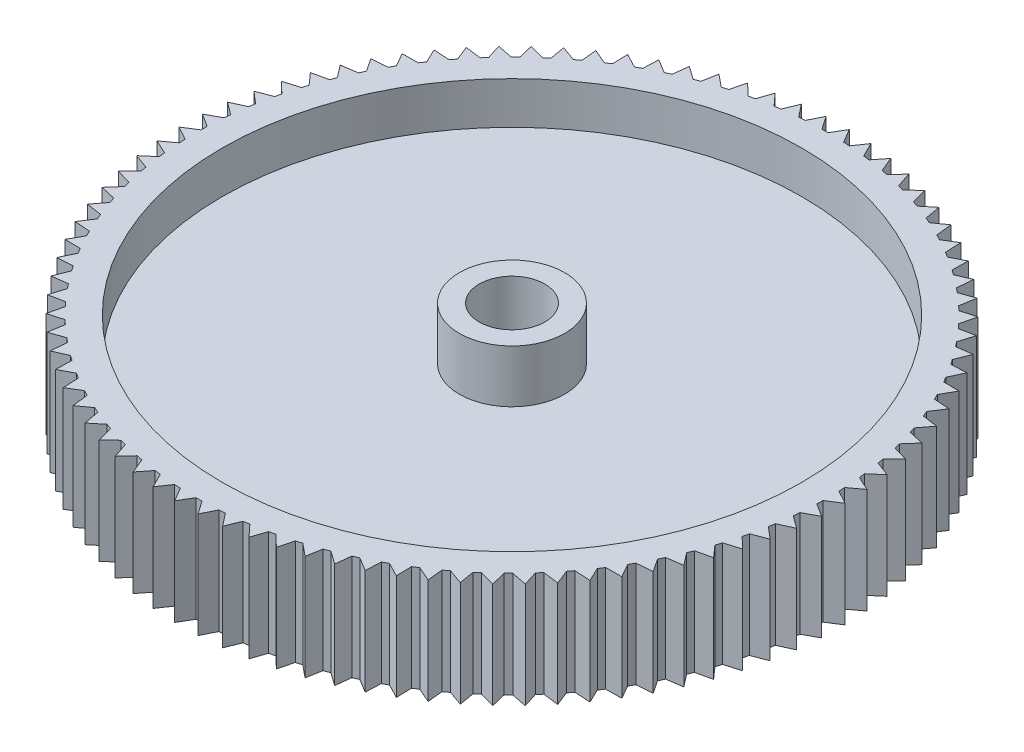
SolidWorks part; units mm, degrees
ref_plane "Front Plane" through (0, 0, 0) normal (0, 0, 1) x (1, 0, 0)
ref_plane "Top Plane" through (0, 0, 0) normal (0, 1, 0) x (1, 0, 0)
ref_plane "Right Plane" through (0, 0, 0) normal (1, 0, 0) x (0, 0, -1)
sketch "Sketch1" plane through (0, 0, 0) normal (0, 1, 0) x (1, 0, 0)
  circle A0 centre (0, 0) radius 12.0584
extrude "Boss-Extrude1" add sketch "Sketch1" along normal blind 10
ref_plane "Plane1" through (0, 5, 0) normal (0, 1, 0) x (1, 0, 0)
sketch "Sketch2" plane through (0, 5, 0) normal (0, 1, 0) x (1, 0, 0)
  circle A0 centre (0, 0) radius 30
  dimension "D1" = 60
extrude "Boss-Extrude3" add sketch "Sketch2" along normal mid plane 10 contours A0
sketch "Sketch3" plane through (0, 10, 0) normal (0, 1, 0) x (1, 0, 0)
  circle A0 centre (0, 0) radius 27.5
  dimension "D1" = 55
extrude "Cut-Extrude1" cut sketch "Sketch3" against normal blind 4
sketch "Sketch4" plane through (0, 0, 0) normal (0, -1, 0) x (1, 0, 0)
  circle A0 centre (0, 0) radius 27.5
  dimension "D1" = 55
extrude "Cut-Extrude2" cut sketch "Sketch4" against normal blind 4
sketch "Sketch5" plane through (0, 6, 0) normal (0, 1, 0) x (1, 0, 0)
  circle A0 centre (0, 0) radius 5
  circle A1 centre (0, 0) radius 3
  dimension "D1" = 10
  dimension "D2" = 6
extrude "Boss-Extrude4" add sketch "Sketch5" along normal mid plane 10 contours A0
sketch "Sketch6" plane through (0, 1, 0) normal (0, -1, 0) x (1, 0, 0)
  circle A0 centre (0, 0) radius 3.1205
extrude "Cut-Extrude3" cut sketch "Sketch6" against normal blind 10
sketch "Sketch8" plane through (0, 10, 0) normal (0, 1, 0) x (1, 0, 0)
  line L0 (0, 30) -> (0.7466, 31.2704)
  line L1 (0.7466, 31.2704) -> (1.5196, 29.9615)
  line L2 (0, 30) -> (1.5196, 29.9615)
  line L3 (2.9261, 31.1421) -> (3.6059, 29.7825)
  line L4 (2.0927, 29.9269) -> (2.9261, 31.1421)
  line L5 (2.0927, 29.9269) -> (3.6059, 29.7825)
  line L6 (5.0913, 30.8621) -> (5.6747, 29.4584)
  line L7 (4.1752, 29.708) -> (5.0913, 30.8621)
  line L8 (4.1752, 29.708) -> (5.6747, 29.4584)
  line L9 (7.2318, 30.4318) -> (7.7157, 28.9908)
  line L10 (6.2374, 29.3444) -> (7.2318, 30.4318)
  line L11 (6.2374, 29.3444) -> (7.7157, 28.9908)
  line L12 (9.337, 29.8532) -> (9.7192, 28.382)
  line L13 (8.2691, 28.8379) -> (9.337, 29.8532)
  line L14 (8.2691, 28.8379) -> (9.7192, 28.382)
  line L15 (11.3967, 29.1292) -> (11.6754, 27.6349)
  line L16 (10.2606, 28.1908) -> (11.3967, 29.1292)
  line L17 (10.2606, 28.1908) -> (11.6754, 27.6349)
  line L18 (13.4009, 28.2632) -> (13.5747, 26.7531)
  line L19 (12.2021, 27.4064) -> (13.4009, 28.2632)
  line L20 (12.2021, 27.4064) -> (13.5747, 26.7531)
  line L21 (15.3398, 27.2596) -> (15.4078, 25.741)
  line L22 (14.0841, 26.4884) -> (15.3398, 27.2596)
  line L23 (14.0841, 26.4884) -> (15.4078, 25.741)
  line L24 (17.2039, 26.1231) -> (17.1659, 24.6035)
  line L25 (15.8976, 25.4414) -> (17.2039, 26.1231)
  line L26 (15.8976, 25.4414) -> (17.1659, 24.6035)
  line L27 (18.9843, 24.8594) -> (18.8403, 23.3461)
  line L28 (17.6336, 24.2705) -> (18.9843, 24.8594)
  line L29 (17.6336, 24.2705) -> (18.8403, 23.3461)
  line L30 (20.6721, 23.4746) -> (20.423, 21.975)
  line L31 (19.2836, 22.9813) -> (20.6721, 23.4746)
  line L32 (19.2836, 22.9813) -> (20.423, 21.975)
  line L33 (22.2593, 21.9754) -> (21.9061, 20.4969)
  line L34 (20.8398, 21.5802) -> (22.2593, 21.9754)
  line L35 (20.8398, 21.5802) -> (21.9061, 20.4969)
  line L36 (23.738, 20.3691) -> (23.2825, 18.9189)
  line L37 (22.2943, 20.0739) -> (23.738, 20.3691)
  line L38 (22.2943, 20.0739) -> (23.2825, 18.9189)
  line L39 (25.101, 18.6636) -> (24.5455, 17.2487)
  line L40 (23.6403, 18.4698) -> (25.101, 18.6636)
  line L41 (23.6403, 18.4698) -> (24.5455, 17.2487)
  line L42 (26.3418, 16.8672) -> (25.689, 15.4944)
  line L43 (24.8711, 16.7758) -> (26.3418, 16.8672)
  line L44 (24.8711, 16.7758) -> (25.689, 15.4944)
  line L45 (27.4542, 14.9886) -> (26.7072, 13.6647)
  line L46 (25.9808, 15) -> (27.4542, 14.9886)
  line L47 (25.9808, 15) -> (26.7072, 13.6647)
  line L48 (28.4329, 13.037) -> (27.5954, 11.7684)
  line L49 (26.9638, 13.1511) -> (28.4329, 13.037)
  line L50 (26.9638, 13.1511) -> (27.5954, 11.7684)
  line L51 (29.2731, 11.0219) -> (28.3491, 9.8148)
  line L52 (27.8155, 11.2382) -> (29.2731, 11.0219)
  line L53 (27.8155, 11.2382) -> (28.3491, 9.8148)
  line L54 (29.9706, 8.953) -> (28.9647, 7.8134)
  line L55 (28.5317, 9.2705) -> (29.9706, 8.953)
  line L56 (28.5317, 9.2705) -> (28.9647, 7.8134)
  line L57 (30.5221, 6.8406) -> (29.4391, 5.7739)
  line L58 (29.1089, 7.2577) -> (30.5221, 6.8406)
  line L59 (29.1089, 7.2577) -> (29.4391, 5.7739)
  line L60 (30.9249, 4.6948) -> (29.7702, 3.7062)
  line L61 (29.5442, 5.2094) -> (30.9249, 4.6948)
  line L62 (29.5442, 5.2094) -> (29.7702, 3.7062)
  line L63 (31.1771, 2.5261) -> (29.9562, 1.6205)
  line L64 (29.8357, 3.1359) -> (31.1771, 2.5261)
  line L65 (29.8357, 3.1359) -> (29.9562, 1.6205)
  line L66 (31.2774, 0.3452) -> (29.9963, -0.473)
  line L67 (29.9817, 1.047) -> (31.2774, 0.3452)
  line L68 (29.9817, 1.047) -> (29.9963, -0.473)
  line L69 (31.2253, -1.8375) -> (29.8902, -2.5643)
  line L70 (29.9817, -1.047) -> (31.2253, -1.8375)
  line L71 (29.9817, -1.047) -> (29.8902, -2.5643)
  line L72 (31.021, -4.0111) -> (29.6385, -4.6431)
  line L73 (29.8357, -3.1359) -> (31.021, -4.0111)
  line L74 (29.8357, -3.1359) -> (29.6385, -4.6431)
  line L75 (30.6656, -6.1653) -> (29.2424, -6.6993)
  line L76 (29.5442, -5.2094) -> (30.6656, -6.1653)
  line L77 (29.5442, -5.2094) -> (29.2424, -6.6993)
  line L78 (30.1609, -8.2894) -> (28.7039, -8.7228)
  line L79 (29.1089, -7.2577) -> (30.1609, -8.2894)
  line L80 (29.1089, -7.2577) -> (28.7039, -8.7228)
  line L81 (29.5092, -10.3731) -> (28.0255, -10.7038)
  line L82 (28.5317, -9.2705) -> (29.5092, -10.3731)
  line L83 (28.5317, -9.2705) -> (28.0255, -10.7038)
  line L84 (28.7137, -12.4063) -> (27.2106, -12.6327)
  line L85 (27.8155, -11.2382) -> (28.7137, -12.4063)
  line L86 (27.8155, -11.2382) -> (27.2106, -12.6327)
  line L87 (27.7783, -14.3791) -> (26.2631, -14.5001)
  line L88 (26.9638, -13.1511) -> (27.7783, -14.3791)
  line L89 (26.9638, -13.1511) -> (26.2631, -14.5001)
  line L90 (26.7076, -16.2818) -> (25.1876, -16.2968)
  line L91 (25.9808, -15) -> (26.7076, -16.2818)
  line L92 (25.9808, -15) -> (25.1876, -16.2968)
  line L93 (25.5068, -18.1051) -> (23.9894, -18.0141)
  line L94 (24.8711, -16.7758) -> (25.5068, -18.1051)
  line L95 (24.8711, -16.7758) -> (23.9894, -18.0141)
  line L96 (24.1817, -19.8403) -> (22.6744, -19.6436)
  line L97 (23.6403, -18.4698) -> (24.1817, -19.8403)
  line L98 (23.6403, -18.4698) -> (22.6744, -19.6436)
  line L99 (22.7388, -21.4788) -> (21.2489, -21.1774)
  line L100 (22.2943, -20.0739) -> (22.7388, -21.4788)
  line L101 (22.2943, -20.0739) -> (21.2489, -21.1774)
  line L102 (21.1852, -23.0126) -> (19.7199, -22.6081)
  line L103 (20.8398, -21.5802) -> (21.1852, -23.0126)
  line L104 (20.8398, -21.5802) -> (19.7199, -22.6081)
  line L105 (19.5283, -24.4344) -> (18.0948, -23.9286)
  line L106 (19.2836, -22.9813) -> (19.5283, -24.4344)
  line L107 (19.2836, -22.9813) -> (18.0948, -23.9286)
  line L108 (17.7762, -25.7371) -> (16.3815, -25.1326)
  line L109 (17.6336, -24.2705) -> (17.7762, -25.7371)
  line L110 (17.6336, -24.2705) -> (16.3815, -25.1326)
  line L111 (15.9376, -26.9144) -> (14.5885, -26.2141)
  line L112 (15.8976, -25.4414) -> (15.9376, -26.9144)
  line L113 (15.8976, -25.4414) -> (14.5885, -26.2141)
  line L114 (14.0213, -27.9606) -> (12.7243, -27.1678)
  line L115 (14.0841, -26.4884) -> (14.0213, -27.9606)
  line L116 (14.0841, -26.4884) -> (12.7243, -27.1678)
  line L117 (12.0368, -28.8706) -> (10.7982, -27.9893)
  line L118 (12.2021, -27.4064) -> (12.0368, -28.8706)
  line L119 (12.2021, -27.4064) -> (10.7982, -27.9893)
  line L120 (9.9935, -29.6399) -> (8.8195, -28.6743)
  line L121 (10.2606, -28.1908) -> (9.9935, -29.6399)
  line L122 (10.2606, -28.1908) -> (8.8195, -28.6743)
  line L123 (7.9016, -30.2648) -> (6.7978, -29.2197)
  line L124 (8.2691, -28.8379) -> (7.9016, -30.2648)
  line L125 (8.2691, -28.8379) -> (6.7978, -29.2197)
  line L126 (5.7712, -30.7423) -> (4.7429, -29.6227)
  line L127 (6.2374, -29.3444) -> (5.7712, -30.7423)
  line L128 (6.2374, -29.3444) -> (4.7429, -29.6227)
  line L129 (3.6127, -31.0699) -> (2.665, -29.8814)
  line L130 (4.1752, -29.708) -> (3.6127, -31.0699)
  line L131 (4.1752, -29.708) -> (2.665, -29.8814)
  line L132 (1.4365, -31.2463) -> (0.5741, -29.9945)
  line L133 (2.0927, -29.9269) -> (1.4365, -31.2463)
  line L134 (2.0927, -29.9269) -> (0.5741, -29.9945)
  line L135 (-0.7466, -31.2704) -> (-1.5196, -29.9615)
  line L136 (0, -30) -> (-0.7466, -31.2704)
  line L137 (0, -30) -> (-1.5196, -29.9615)
  line L138 (-2.9261, -31.1421) -> (-3.6059, -29.7825)
  line L139 (-2.0927, -29.9269) -> (-2.9261, -31.1421)
  line L140 (-2.0927, -29.9269) -> (-3.6059, -29.7825)
  line L141 (-5.0913, -30.8621) -> (-5.6747, -29.4584)
  line L142 (-4.1752, -29.708) -> (-5.0913, -30.8621)
  line L143 (-4.1752, -29.708) -> (-5.6747, -29.4584)
  line L144 (-7.2318, -30.4318) -> (-7.7157, -28.9908)
  line L145 (-6.2374, -29.3444) -> (-7.2318, -30.4318)
  line L146 (-6.2374, -29.3444) -> (-7.7157, -28.9908)
  line L147 (-9.337, -29.8532) -> (-9.7192, -28.382)
  line L148 (-8.2691, -28.8379) -> (-9.337, -29.8532)
  line L149 (-8.2691, -28.8379) -> (-9.7192, -28.382)
  line L150 (-11.3967, -29.1292) -> (-11.6754, -27.6349)
  line L151 (-10.2606, -28.1908) -> (-11.3967, -29.1292)
  line L152 (-10.2606, -28.1908) -> (-11.6754, -27.6349)
  line L153 (-13.4009, -28.2632) -> (-13.5747, -26.7531)
  line L154 (-12.2021, -27.4064) -> (-13.4009, -28.2632)
  line L155 (-12.2021, -27.4064) -> (-13.5747, -26.7531)
  line L156 (-15.3398, -27.2596) -> (-15.4078, -25.741)
  line L157 (-14.0841, -26.4884) -> (-15.3398, -27.2596)
  line L158 (-14.0841, -26.4884) -> (-15.4078, -25.741)
  line L159 (-17.2039, -26.1231) -> (-17.1659, -24.6035)
  line L160 (-15.8976, -25.4414) -> (-17.2039, -26.1231)
  line L161 (-15.8976, -25.4414) -> (-17.1659, -24.6035)
  line L162 (-18.9843, -24.8594) -> (-18.8403, -23.3461)
  line L163 (-17.6336, -24.2705) -> (-18.9843, -24.8594)
  line L164 (-17.6336, -24.2705) -> (-18.8403, -23.3461)
  line L165 (-20.6721, -23.4746) -> (-20.423, -21.975)
  line L166 (-19.2836, -22.9813) -> (-20.6721, -23.4746)
  line L167 (-19.2836, -22.9813) -> (-20.423, -21.975)
  line L168 (-22.2593, -21.9754) -> (-21.9061, -20.4969)
  line L169 (-20.8398, -21.5802) -> (-22.2593, -21.9754)
  line L170 (-20.8398, -21.5802) -> (-21.9061, -20.4969)
  line L171 (-23.738, -20.3691) -> (-23.2825, -18.9189)
  line L172 (-22.2943, -20.0739) -> (-23.738, -20.3691)
  line L173 (-22.2943, -20.0739) -> (-23.2825, -18.9189)
  line L174 (-25.101, -18.6636) -> (-24.5455, -17.2487)
  line L175 (-23.6403, -18.4698) -> (-25.101, -18.6636)
  line L176 (-23.6403, -18.4698) -> (-24.5455, -17.2487)
  line L177 (-26.3418, -16.8672) -> (-25.689, -15.4944)
  line L178 (-24.8711, -16.7758) -> (-26.3418, -16.8672)
  line L179 (-24.8711, -16.7758) -> (-25.689, -15.4944)
  line L180 (-27.4542, -14.9886) -> (-26.7072, -13.6647)
  line L181 (-25.9808, -15) -> (-27.4542, -14.9886)
  line L182 (-25.9808, -15) -> (-26.7072, -13.6647)
  line L183 (-28.4329, -13.037) -> (-27.5954, -11.7684)
  line L184 (-26.9638, -13.1511) -> (-28.4329, -13.037)
  line L185 (-26.9638, -13.1511) -> (-27.5954, -11.7684)
  line L186 (-29.2731, -11.0219) -> (-28.3491, -9.8148)
  line L187 (-27.8155, -11.2382) -> (-29.2731, -11.0219)
  line L188 (-27.8155, -11.2382) -> (-28.3491, -9.8148)
  line L189 (-29.9706, -8.953) -> (-28.9647, -7.8134)
  line L190 (-28.5317, -9.2705) -> (-29.9706, -8.953)
  line L191 (-28.5317, -9.2705) -> (-28.9647, -7.8134)
  line L192 (-30.5221, -6.8406) -> (-29.4391, -5.7739)
  line L193 (-29.1089, -7.2577) -> (-30.5221, -6.8406)
  line L194 (-29.1089, -7.2577) -> (-29.4391, -5.7739)
  line L195 (-30.9249, -4.6948) -> (-29.7702, -3.7062)
  line L196 (-29.5442, -5.2094) -> (-30.9249, -4.6948)
  line L197 (-29.5442, -5.2094) -> (-29.7702, -3.7062)
  line L198 (-31.1771, -2.5261) -> (-29.9562, -1.6205)
  line L199 (-29.8357, -3.1359) -> (-31.1771, -2.5261)
  line L200 (-29.8357, -3.1359) -> (-29.9562, -1.6205)
  line L201 (-31.2774, -0.3452) -> (-29.9963, 0.473)
  line L202 (-29.9817, -1.047) -> (-31.2774, -0.3452)
  line L203 (-29.9817, -1.047) -> (-29.9963, 0.473)
  line L204 (-31.2253, 1.8375) -> (-29.8902, 2.5643)
  line L205 (-29.9817, 1.047) -> (-31.2253, 1.8375)
  line L206 (-29.9817, 1.047) -> (-29.8902, 2.5643)
  line L207 (-31.021, 4.0111) -> (-29.6385, 4.6431)
  line L208 (-29.8357, 3.1359) -> (-31.021, 4.0111)
  line L209 (-29.8357, 3.1359) -> (-29.6385, 4.6431)
  line L210 (-30.6656, 6.1653) -> (-29.2424, 6.6993)
  line L211 (-29.5442, 5.2094) -> (-30.6656, 6.1653)
  line L212 (-29.5442, 5.2094) -> (-29.2424, 6.6993)
  line L213 (-30.1609, 8.2894) -> (-28.7039, 8.7228)
  line L214 (-29.1089, 7.2577) -> (-30.1609, 8.2894)
  line L215 (-29.1089, 7.2577) -> (-28.7039, 8.7228)
  line L216 (-29.5092, 10.3731) -> (-28.0255, 10.7038)
  line L217 (-28.5317, 9.2705) -> (-29.5092, 10.3731)
  line L218 (-28.5317, 9.2705) -> (-28.0255, 10.7038)
  line L219 (-28.7137, 12.4063) -> (-27.2106, 12.6327)
  line L220 (-27.8155, 11.2382) -> (-28.7137, 12.4063)
  line L221 (-27.8155, 11.2382) -> (-27.2106, 12.6327)
  line L222 (-27.7783, 14.3791) -> (-26.2631, 14.5001)
  line L223 (-26.9638, 13.1511) -> (-27.7783, 14.3791)
  line L224 (-26.9638, 13.1511) -> (-26.2631, 14.5001)
  line L225 (-26.7076, 16.2818) -> (-25.1876, 16.2968)
  line L226 (-25.9808, 15) -> (-26.7076, 16.2818)
  line L227 (-25.9808, 15) -> (-25.1876, 16.2968)
  line L228 (-25.5068, 18.1051) -> (-23.9894, 18.0141)
  line L229 (-24.8711, 16.7758) -> (-25.5068, 18.1051)
  line L230 (-24.8711, 16.7758) -> (-23.9894, 18.0141)
  line L231 (-24.1817, 19.8403) -> (-22.6744, 19.6436)
  line L232 (-23.6403, 18.4698) -> (-24.1817, 19.8403)
  line L233 (-23.6403, 18.4698) -> (-22.6744, 19.6436)
  line L234 (-22.7388, 21.4788) -> (-21.2489, 21.1774)
  line L235 (-22.2943, 20.0739) -> (-22.7388, 21.4788)
  line L236 (-22.2943, 20.0739) -> (-21.2489, 21.1774)
  line L237 (-21.1852, 23.0126) -> (-19.7199, 22.6081)
  line L238 (-20.8398, 21.5802) -> (-21.1852, 23.0126)
  line L239 (-20.8398, 21.5802) -> (-19.7199, 22.6081)
  line L240 (-19.5283, 24.4344) -> (-18.0948, 23.9286)
  line L241 (-19.2836, 22.9813) -> (-19.5283, 24.4344)
  line L242 (-19.2836, 22.9813) -> (-18.0948, 23.9286)
  line L243 (-17.7762, 25.7371) -> (-16.3815, 25.1326)
  line L244 (-17.6336, 24.2705) -> (-17.7762, 25.7371)
  line L245 (-17.6336, 24.2705) -> (-16.3815, 25.1326)
  line L246 (-15.9376, 26.9144) -> (-14.5885, 26.2141)
  line L247 (-15.8976, 25.4414) -> (-15.9376, 26.9144)
  line L248 (-15.8976, 25.4414) -> (-14.5885, 26.2141)
  line L249 (-14.0213, 27.9606) -> (-12.7243, 27.1678)
  line L250 (-14.0841, 26.4884) -> (-14.0213, 27.9606)
  line L251 (-14.0841, 26.4884) -> (-12.7243, 27.1678)
  line L252 (-12.0368, 28.8706) -> (-10.7982, 27.9893)
  line L253 (-12.2021, 27.4064) -> (-12.0368, 28.8706)
  line L254 (-12.2021, 27.4064) -> (-10.7982, 27.9893)
  line L255 (-9.9935, 29.6399) -> (-8.8195, 28.6743)
  line L256 (-10.2606, 28.1908) -> (-9.9935, 29.6399)
  line L257 (-10.2606, 28.1908) -> (-8.8195, 28.6743)
  line L258 (-7.9016, 30.2648) -> (-6.7978, 29.2197)
  line L259 (-8.2691, 28.8379) -> (-7.9016, 30.2648)
  line L260 (-8.2691, 28.8379) -> (-6.7978, 29.2197)
  line L261 (-5.7712, 30.7423) -> (-4.7429, 29.6227)
  line L262 (-6.2374, 29.3444) -> (-5.7712, 30.7423)
  line L263 (-6.2374, 29.3444) -> (-4.7429, 29.6227)
  line L264 (-3.6127, 31.0699) -> (-2.665, 29.8814)
  line L265 (-4.1752, 29.708) -> (-3.6127, 31.0699)
  line L266 (-4.1752, 29.708) -> (-2.665, 29.8814)
  line L267 (-1.4365, 31.2463) -> (-0.5741, 29.9945)
  line L268 (-2.0927, 29.9269) -> (-1.4365, 31.2463)
  line L269 (-2.0927, 29.9269) -> (-0.5741, 29.9945)
  circle A0 centre (0, 0) radius 30 construction
  point P274 (0, 0)
  dimension "D1" = 90
extrude "Boss-Extrude5" add sketch "Sketch8" against normal blind 10
